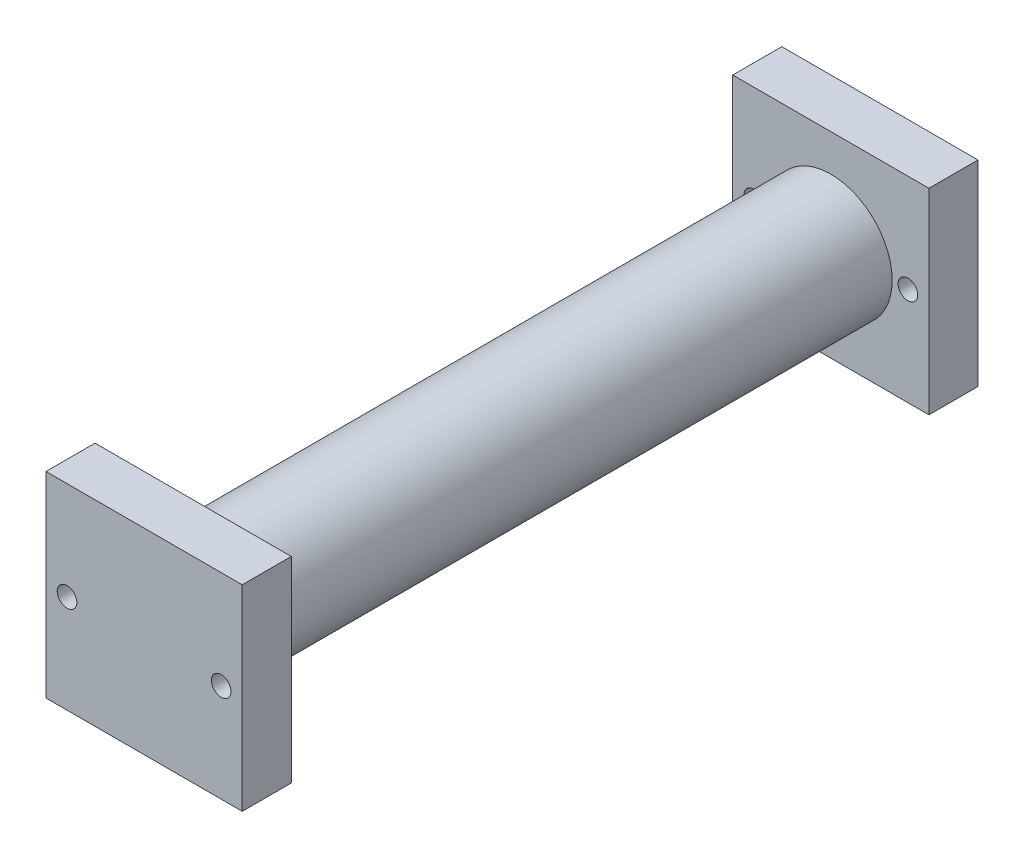
SolidWorks part; units mm, degrees
ref_plane "前基準面" through (0, 0, 0) normal (0, 0, 1) x (1, 0, 0)
ref_plane "上基準面" through (0, 0, 0) normal (0, 1, 0) x (1, 0, 0)
ref_plane "右基準面" through (0, 0, 0) normal (1, 0, 0) x (0, 0, -1)
sketch "草圖1" plane through (0, 0, 0) normal (0, 0, 1) x (1, 0, 0)
  line L1 (-20, 20) -> (20, 20)
  line L2 (-20, 20) -> (-20, -20)
  line L3 (-20, -20) -> (20, -20)
  line L4 (20, 20) -> (20, -20)
  line L5 (-20, 20) -> (20, -20) construction
  line L6 (-20, -20) -> (20, 20) construction
  point P0 (0, 0)
extrude "填料-伸長1" add sketch "草圖1" along normal blind 10
sketch "草圖2" plane through (0, 0, 10) normal (0, 0, 1) x (1, 0, 0)
  circle A0 centre (0, 0) radius 12.5
extrude "填料-伸長2" add sketch "草圖2" along normal blind 130
sketch "草圖3" plane through (0, 0, 140) normal (0, 0, 1) x (1, 0, 0)
  line L1 (-20, 20) -> (20, 20)
  line L2 (-20, 20) -> (-20, -20)
  line L3 (-20, -20) -> (20, -20)
  line L4 (20, 20) -> (20, -20)
  line L5 (-20, 20) -> (20, -20) construction
  line L6 (-20, -20) -> (20, 20) construction
  point P0 (0, 0)
extrude "填料-伸長3" add sketch "草圖3" along normal blind 10
sketch "草圖4" plane through (0, 0, 150) normal (0, 0, 1) x (1, 0, 0)
  line L0 (15.714, 0) -> (-15.714, 0)
  circle A0 centre (-15.714, 0) radius 2
  circle A1 centre (15.714, 0) radius 2
  point P4 (0, 0)
extrude "除料-伸長1" cut sketch "草圖4" against normal blind 10
sketch "草圖5" plane through (0, 0, 150) normal (0, 0, 1) x (1, 0, 0)
  line L0 (0, 0) -> (15.71, 0)
  circle A0 centre (15.71, 0) radius 2
extrude "除料-伸長2" cut sketch "草圖5" against normal blind 10
sketch "草圖6" plane through (0, 0, 0) normal (0, 0, -1) x (-1, 0, 0)
  line L0 (0, 0) -> (-15.71, 0)
  circle A0 centre (-15.71, 0) radius 2
  point P4 (0, 0)
extrude "除料-伸長3" cut sketch "草圖6" against normal blind 10
sketch "草圖7" plane through (0, 0, 0) normal (0, 0, -1) x (-1, 0, 0)
  line L0 (0, 0) -> (15.71, 0)
  circle A0 centre (15.71, 0) radius 2
extrude "除料-伸長4" cut sketch "草圖7" against normal blind 10
